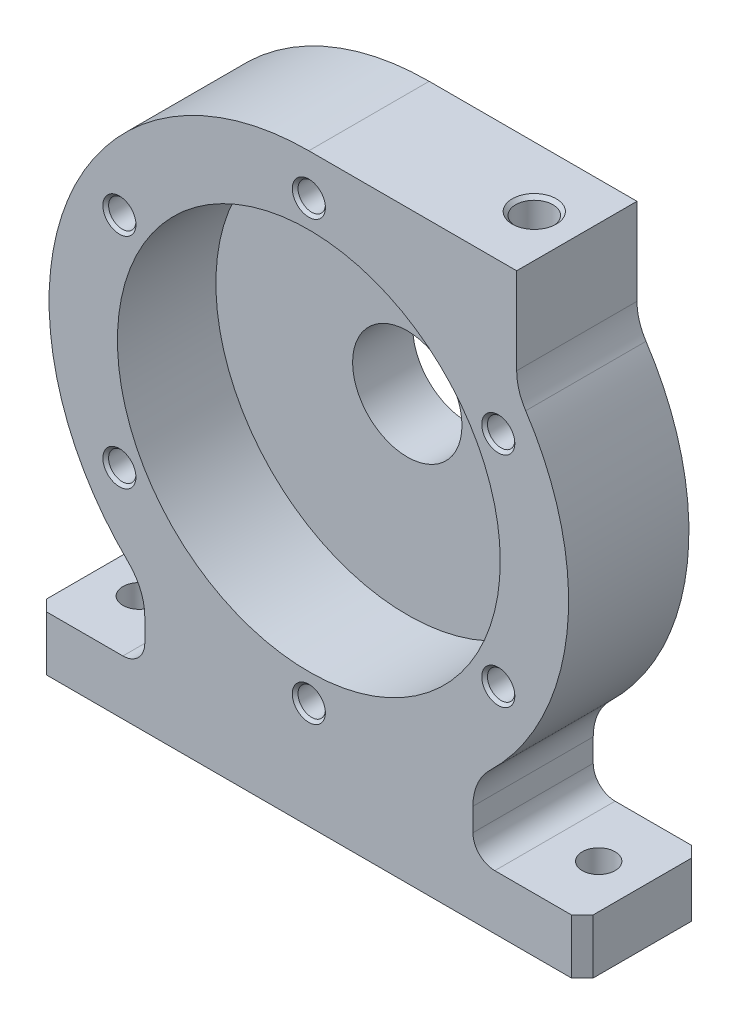
SolidWorks part; units mm, degrees
ref_plane "Front Plane" through (0, 0, 0) normal (0, 0, 1) x (1, 0, 0)
ref_plane "Top Plane" through (0, 0, 0) normal (0, 1, 0) x (1, 0, 0)
ref_plane "Right Plane" through (0, 0, 0) normal (1, 0, 0) x (0, 0, -1)
sketch "Sketch1" plane through (0, 0, 0) normal (0, 0, 1) x (1, 0, 0)
  line L0 (0, 0) -> (0, -59.5) construction
  line L1 (-50, -59.5) -> (50, -59.5)
  line L2 (50, -59.5) -> (50, -49.5)
  line L3 (50, -49.5) -> (34, -49.5)
  line L4 (30, -45.5) -> (30, -41.3068)
  line L5 (0, 47.5) -> (38, 47.5)
  line L6 (38, 47.5) -> (38, 31.6583)
  line L7 (-30, -45.5) -> (-30, -41.3068)
  line L8 (-50, -49.5) -> (-34, -49.5)
  line L9 (-50, -59.5) -> (-50, -49.5)
  arc A0 (33.0435, -34.123) -> (39.6522, 26.1525) centre (0, 0) ccw
  arc A1 (0, 47.5) -> (-33.0435, -34.123) centre (0, 0) ccw
  arc A2 (30, -41.3068) -> (33.0435, -34.123) centre (40, -41.3068) cw
  arc A3 (38, 31.6583) -> (39.6522, 26.1525) centre (48, 31.6583) ccw
  arc A4 (34, -49.5) -> (30, -45.5) centre (34, -45.5) cw
  arc A5 (-30, -41.3068) -> (-33.0435, -34.123) centre (-40, -41.3068) ccw
  arc A6 (-34, -49.5) -> (-30, -45.5) centre (-34, -45.5) ccw
  dimension "D1" = 95
  dimension "D7" = 10
  dimension "D8" = 4
  dimension "D2" = 38
  dimension "D3" = 50
  dimension "D4" = 10
  dimension "D5" = 59.5
  dimension "D6" = 30
extrude "Boss-Extrude1" add sketch "Sketch1" along normal blind 22
sketch "Sketch2" plane through (0, 0, 22) normal (0, 0, 1) x (1, 0, 0)
  circle A0 centre (0, 0) radius 35
  dimension "D1" = 70
extrude "Cut-Extrude1" cut sketch "Sketch2" against normal blind 18
sketch "Sketch3" plane through (0, 0, 0) normal (0, 0, -1) x (-1, 0, 0)
  circle A0 centre (0, 0) radius 14
  dimension "D1" = 28
extrude "Boss-Extrude2" add sketch "Sketch3" along normal blind 7
fillet "Fillet1" radius 4 1 edges at (-14, 0, 0)
sketch "Sketch4" plane through (0, 0, -7) normal (0, 0, -1) x (-1, 0, 0)
  circle A0 centre (0, 0) radius 10
  dimension "D1" = 20
extrude "Cut-Extrude2" cut sketch "Sketch4" against normal through all
chamfer "Chamfer1" distance 2 angle 45 4 edges at (50, -54.5, 0) (50, -54.5, 22) (-50, -54.5, 22) (-50, -54.5, 0)
sketch "Sketch5" plane through (0, 47.5, 0) normal (0, 1, 0) x (1, 0, 0)
  line L0 (38, -11) -> (0, -11) construction
  line L1 (38, -22) -> (38, 0) construction
  line L2 (0, -22) -> (0, 0) construction
hole_wizard "M8x1.25 Tapped Hole1" positions "Sketch6" profile "Sketch7" tap size "M8x1.25" standard "ANSI Metric"
sketch "Sketch6" plane through (0, 47.5, 0) normal (0, 1, 0) x (1, 0, 0)
  line L0 (38, -11) -> (0, -11) construction
  point P0 (30.2241, -11)
  dimension "D1" = 7.7759
sketch "Sketch7" plane through (30.2241, 47.5, 11) normal (1, 0, 0) x (0, 0, 1)
  line L0 (0, 0) -> (0, 31.7929)
  line L1 (0, 31.7929) -> (3.4, 29.75)
  line L2 (3.4, 29.75) -> (3.4, 0.625)
  line L3 (3.4, 0.625) -> (4.025, 0)
  line L5 (4.025, 0) -> (0, 0)
  line L6 (-3.4, 0.625) -> (-4.025, 0) construction
  line L10 (0, 31.7929) -> (-3.4, 29.75) construction
  line L11 (0, -6.35) -> (0, 107.95) construction
  dimension "Tap Drill Dia." = 6.8
  dimension "Tap Drill Depth" = 29.75
  dimension "Near C'Sink Dia." = 8.05
  dimension "Near C'Sink Angle" = 90
  dimension "Drill Angle" = 118
cosmetic thread "Hole Thread1" parameters "D1"=16, "D2"=8
sketch "Sketch8" plane through (0, 0, 22) normal (0, 0, 1) x (1, 0, 0)
  circle A0 centre (0, 0) radius 40 construction
  dimension "D1" = 80
hole_wizard "M6x1.0 Tapped Hole1" positions "Sketch9" profile "Sketch10" tap size "M6x1.0" standard "ANSI Metric"
sketch "Sketch9" plane through (0, 0, 22) normal (0, 0, 1) x (1, 0, 0)
  circle A0 centre (0, 0) radius 40 construction
  point P0 (0, 40)
sketch "Sketch10" plane through (0, 40, 22) normal (1, 0, 0) x (0, -1, 0)
  line L0 (0, 0) -> (0, 16.5022)
  line L1 (0, 16.5022) -> (2.5, 15)
  line L2 (2.5, 15) -> (2.5, 0.525)
  line L3 (2.5, 0.525) -> (3.025, 0)
  line L5 (3.025, 0) -> (0, 0)
  line L6 (-2.5, 0.525) -> (-3.025, 0) construction
  line L10 (0, 16.5022) -> (-2.5, 15) construction
  line L11 (0, -6.35) -> (0, 107.95) construction
  dimension "Tap Drill Dia." = 5
  dimension "Tap Drill Depth" = 15
  dimension "Near C'Sink Dia." = 6.05
  dimension "Near C'Sink Angle" = 90
  dimension "Drill Angle" = 118
cosmetic thread "Hole Thread2" parameters "D1"=12, "D2"=6
pattern_circular "CirPattern1" count 6 over 360 about axis through (0, 0, 0) along (0, 0, 1) of "M6x1.0 Tapped Hole1"
hole_wizard "CSK for M8 Countersunk Flat Head Screw1" positions "Sketch14" profile "Sketch15" countersink size "M8" standard "ISO"
sketch "Sketch14" plane through (0, -59.5, 0) normal (0, -1, 0) x (-1, 0, 0)
  line L0 (-50, -20) -> (-50, -2) construction
  line L1 (50, -20) -> (50, -2) construction
  point P0 (42, -11)
  point P2 (-42, -11)
  point P12 (0, 0)
  point P13 (50, -11)
  point P14 (0, 0)
  point P15 (-50, -11)
  dimension "D1" = 8
  dimension "D2" = 8
sketch "Sketch15" plane through (-42, -59.5, 11) normal (1, 0, 0) x (0, 0, -1)
  line L0 (0, 0) -> (0, 21.8026)
  line L1 (0, 21.8026) -> (3, 20)
  line L2 (3, 20) -> (3, 1)
  line L3 (3, 1) -> (4, 0)
  line L5 (4, 0) -> (0, 0)
  line L6 (-3, 1) -> (-4, 0) construction
  line L10 (0, 21.8026) -> (-3, 20) construction
  line L11 (0, -6.35) -> (0, 107.95) construction
  dimension "Hole Dia." = 6
  dimension "Hole Depth" = 20
  dimension "Near C'Sink Dia." = 8
  dimension "Near C'Sink Angle" = 90
  dimension "Drill Angle" = 118
